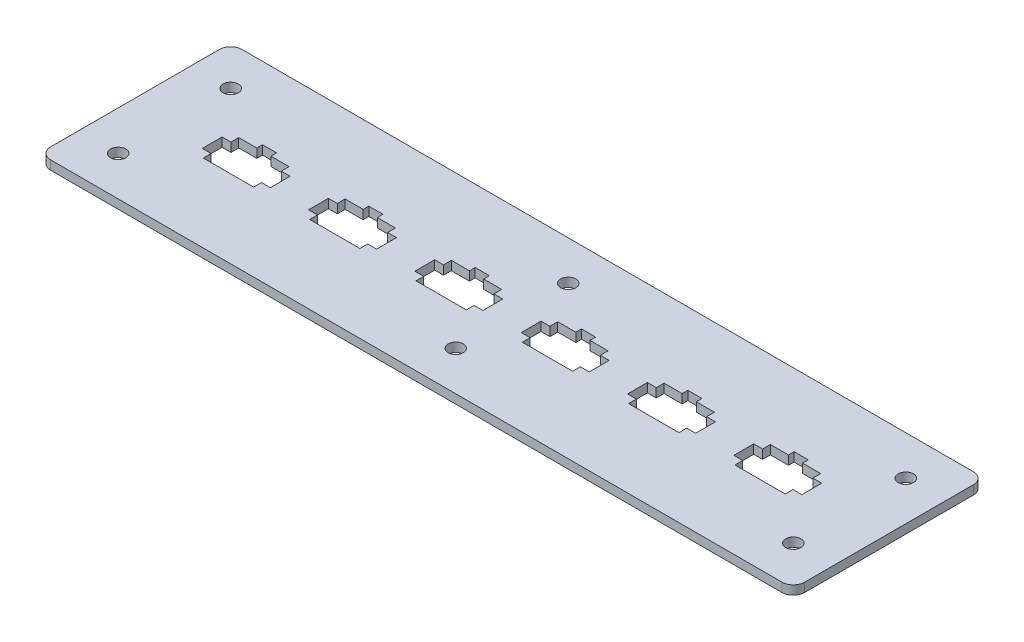
SolidWorks part; units mm, degrees
ref_plane "Front Plane" through (0, 0, 0) normal (0, 0, 1) x (1, 0, 0)
ref_plane "Top Plane" through (0, 0, 0) normal (0, 1, 0) x (1, 0, 0)
ref_plane "Right Plane" through (0, 0, 0) normal (1, 0, 0) x (0, 0, -1)
sketch "Sketch1" plane through (0, 0, 0) normal (0, 1, 0) x (1, 0, 0)
  line L0 (-2, 9.4) -> (2, 9.4)
  line L1 (2, 9.4) -> (2, 7.8)
  line L2 (2, 7.8) -> (7.1, 7.8)
  line L3 (7.1, 7.8) -> (7.1, 5.6)
  line L4 (7.1, 5.6) -> (9.6, 5.6)
  line L5 (9.6, 5.6) -> (9.6, 0)
  line L6 (9.6, 0) -> (7.1, 0)
  line L7 (7.1, 0) -> (7.1, -2.2)
  line L8 (7.1, -2.2) -> (-7.1, -2.2)
  line L9 (0, 9.4) -> (0, -2.2) construction
  line L10 (-7.1, 0) -> (-7.1, -2.2)
  line L11 (-9.6, 0) -> (-7.1, 0)
  line L12 (-9.6, 5.6) -> (-9.6, 0)
  line L13 (-7.1, 5.6) -> (-9.6, 5.6)
  line L14 (-7.1, 7.8) -> (-7.1, 5.6)
  line L15 (-2, 7.8) -> (-7.1, 7.8)
  line L16 (-2, 9.4) -> (-2, 7.8)
  line L17 (28, 9.4) -> (32, 9.4)
  line L18 (32, 9.4) -> (32, 7.8)
  line L19 (32, 7.8) -> (37.1, 7.8)
  line L20 (37.1, 7.8) -> (37.1, 5.6)
  line L21 (37.1, 5.6) -> (39.6, 5.6)
  line L22 (39.6, 5.6) -> (39.6, 0)
  line L23 (39.6, 0) -> (37.1, 0)
  line L24 (37.1, 0) -> (37.1, -2.2)
  line L25 (37.1, -2.2) -> (22.9, -2.2)
  line L26 (22.9, 0) -> (22.9, -2.2)
  line L27 (20.4, 0) -> (22.9, 0)
  line L28 (20.4, 5.6) -> (20.4, 0)
  line L29 (22.9, 5.6) -> (20.4, 5.6)
  line L30 (22.9, 7.8) -> (22.9, 5.6)
  line L31 (28, 7.8) -> (22.9, 7.8)
  line L32 (28, 9.4) -> (28, 7.8)
  line L33 (30, 9.4) -> (30, -2.2) construction
  line L34 (58, 9.4) -> (62, 9.4)
  line L35 (62, 9.4) -> (62, 7.8)
  line L36 (62, 7.8) -> (67.1, 7.8)
  line L37 (67.1, 7.8) -> (67.1, 5.6)
  line L38 (67.1, 5.6) -> (69.6, 5.6)
  line L39 (69.6, 5.6) -> (69.6, 0)
  line L40 (69.6, 0) -> (67.1, 0)
  line L41 (67.1, 0) -> (67.1, -2.2)
  line L42 (67.1, -2.2) -> (52.9, -2.2)
  line L43 (52.9, 0) -> (52.9, -2.2)
  line L44 (50.4, 0) -> (52.9, 0)
  line L45 (50.4, 5.6) -> (50.4, 0)
  line L46 (52.9, 5.6) -> (50.4, 5.6)
  line L47 (52.9, 7.8) -> (52.9, 5.6)
  line L48 (58, 7.8) -> (52.9, 7.8)
  line L49 (58, 9.4) -> (58, 7.8)
  line L50 (60, 9.4) -> (60, -2.2) construction
  line L51 (88, 9.4) -> (92, 9.4)
  line L52 (92, 9.4) -> (92, 7.8)
  line L53 (92, 7.8) -> (97.1, 7.8)
  line L54 (97.1, 7.8) -> (97.1, 5.6)
  line L55 (97.1, 5.6) -> (99.6, 5.6)
  line L56 (99.6, 5.6) -> (99.6, 0)
  line L57 (99.6, 0) -> (97.1, 0)
  line L58 (97.1, 0) -> (97.1, -2.2)
  line L59 (97.1, -2.2) -> (82.9, -2.2)
  line L60 (82.9, 0) -> (82.9, -2.2)
  line L61 (80.4, 0) -> (82.9, 0)
  line L62 (80.4, 5.6) -> (80.4, 0)
  line L63 (82.9, 5.6) -> (80.4, 5.6)
  line L64 (82.9, 7.8) -> (82.9, 5.6)
  line L65 (88, 7.8) -> (82.9, 7.8)
  line L66 (88, 9.4) -> (88, 7.8)
  line L67 (90, 9.4) -> (90, -2.2) construction
  line L68 (118, 9.4) -> (122, 9.4)
  line L69 (122, 9.4) -> (122, 7.8)
  line L70 (122, 7.8) -> (127.1, 7.8)
  line L71 (127.1, 7.8) -> (127.1, 5.6)
  line L72 (127.1, 5.6) -> (129.6, 5.6)
  line L73 (129.6, 5.6) -> (129.6, 0)
  line L74 (129.6, 0) -> (127.1, 0)
  line L75 (127.1, 0) -> (127.1, -2.2)
  line L76 (127.1, -2.2) -> (112.9, -2.2)
  line L77 (112.9, 0) -> (112.9, -2.2)
  line L78 (110.4, 0) -> (112.9, 0)
  line L79 (110.4, 5.6) -> (110.4, 0)
  line L80 (112.9, 5.6) -> (110.4, 5.6)
  line L81 (112.9, 7.8) -> (112.9, 5.6)
  line L82 (118, 7.8) -> (112.9, 7.8)
  line L83 (118, 9.4) -> (118, 7.8)
  line L84 (120, 9.4) -> (120, -2.2) construction
  line L85 (148, 9.4) -> (152, 9.4)
  line L86 (152, 9.4) -> (152, 7.8)
  line L87 (152, 7.8) -> (157.1, 7.8)
  line L88 (157.1, 7.8) -> (157.1, 5.6)
  line L89 (157.1, 5.6) -> (159.6, 5.6)
  line L90 (159.6, 5.6) -> (159.6, 0)
  line L91 (159.6, 0) -> (157.1, 0)
  line L92 (157.1, 0) -> (157.1, -2.2)
  line L93 (157.1, -2.2) -> (142.9, -2.2)
  line L94 (142.9, 0) -> (142.9, -2.2)
  line L95 (140.4, 0) -> (142.9, 0)
  line L96 (140.4, 5.6) -> (140.4, 0)
  line L97 (142.9, 5.6) -> (140.4, 5.6)
  line L98 (142.9, 7.8) -> (142.9, 5.6)
  line L99 (148, 7.8) -> (142.9, 7.8)
  line L100 (148, 9.4) -> (148, 7.8)
  line L101 (150, 9.4) -> (150, -2.2) construction
  line L102 (-2, 9.4) -> (28, 9.4) construction
  line L103 (69.6, 2.8) -> (80.4, 2.8) construction
  line L104 (75, 15.5) -> (75, -9.9) construction
  line L105 (-28.1875, 29.7875) -> (178.1875, 29.7875)
  line L106 (-31.3625, 26.6125) -> (-31.3625, -21.0125)
  line L107 (-28.1875, -24.1875) -> (178.1875, -24.1875)
  line L108 (181.3625, 26.6125) -> (181.3625, -21.0125)
  line L109 (-31.3625, 29.7875) -> (181.3625, -24.1875) construction
  line L110 (-31.3625, -24.1875) -> (181.3625, 29.7875) construction
  line L111 (-17.075, -9.9) -> (167.075, -9.9) construction
  line L112 (-17.075, -9.9) -> (-17.075, 15.5) construction
  line L113 (-17.075, 15.5) -> (167.075, 15.5) construction
  line L114 (167.075, -9.9) -> (167.075, 15.5) construction
  line L115 (-17.075, -9.9) -> (167.075, 15.5) construction
  line L116 (-17.075, 15.5) -> (167.075, -9.9) construction
  line L117 (-17.075, 2.8) -> (167.075, 2.8) construction
  circle A0 centre (170.25, 18.675) radius 2.1527
  circle A1 centre (-20.25, 18.675) radius 2.1527
  circle A2 centre (170.25, -13.075) radius 2.1527
  circle A3 centre (75, -13.075) radius 2.1527
  circle A4 centre (75, 18.675) radius 2.1527
  circle A5 centre (-20.25, -13.075) radius 2.1527
  arc A6 (178.1875, 29.7875) -> (181.3625, 26.6125) centre (178.1875, 26.6125) cw
  arc A7 (181.3625, -21.0125) -> (178.1875, -24.1875) centre (178.1875, -21.0125) cw
  arc A8 (-28.1875, -24.1875) -> (-31.3625, -21.0125) centre (-28.1875, -21.0125) cw
  arc A9 (-28.1875, 29.7875) -> (-31.3625, 26.6125) centre (-28.1875, 26.6125) ccw
  point P5 (0, 3.6)
  point P20 (-9.6, 2.8)
  point P115 (75, 2.8)
  point P122 (75, 2.8)
  dimension "D11" = 4.3053
  dimension "D19" = 4.3053
  dimension "D20" = 3.175
  dimension "D1" = 5.6
  dimension "D2" = 10
  dimension "D3" = 11.6
  dimension "D4" = 4
  dimension "D5" = 19.2
  dimension "D6" = 14.2
  dimension "D8" = 30
  dimension "D9" = 53.975
  dimension "D10" = 212.725
  dimension "D12" = 3.175
  dimension "D13" = 3.175
  dimension "D14" = 14.2875
  dimension "D15" = 14.2875
  dimension "D16" = 25.4
  dimension "D17" = 184.15
  dimension "D18" = 3.175
  dimension "D7" = 6
extrude "Boss-Extrude1" add sketch "Sketch1" along normal blind 2.54 contours L105 L108 L107 L106
